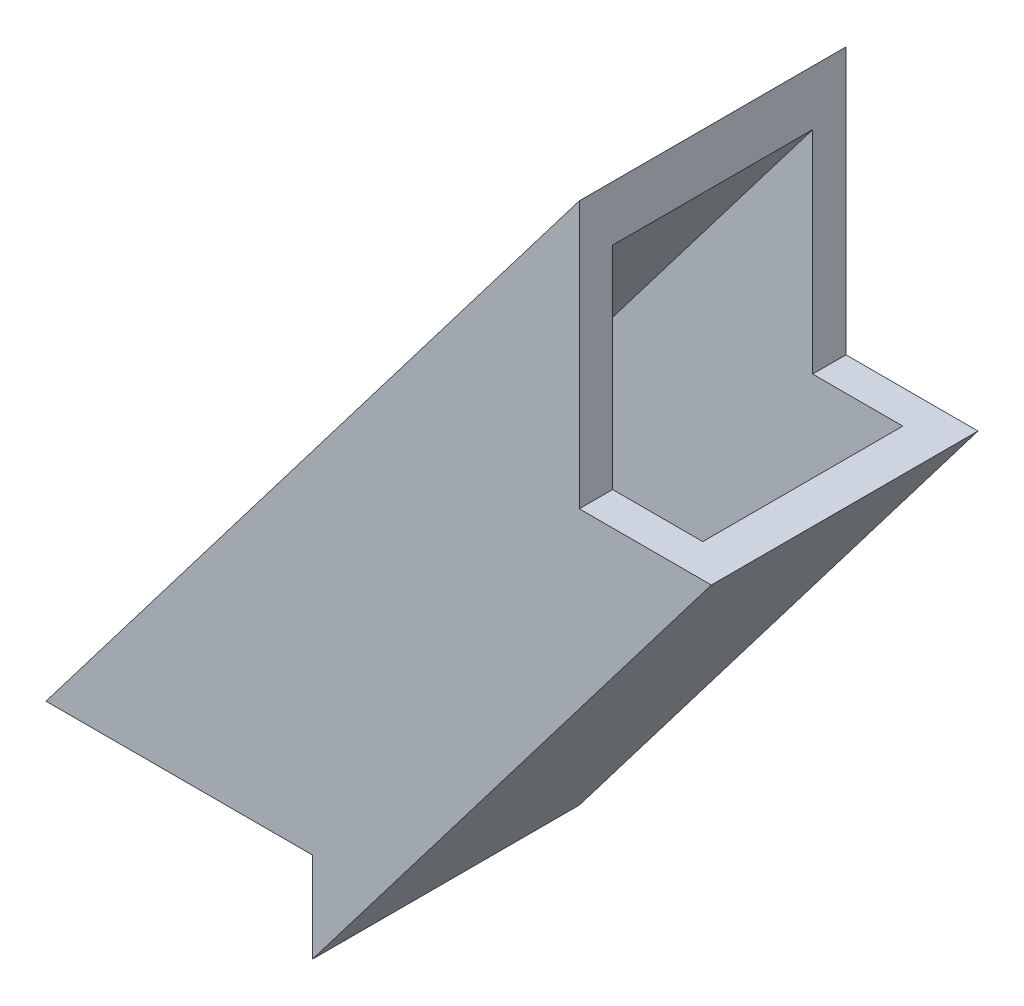
SolidWorks part; units mm, degrees
material "6061-T6 (SS)"
ref_plane "Front Plane" through (0, 0, 0) normal (0, 0, 1) x (1, 0, 0)
ref_plane "Top Plane" through (0, 0, 0) normal (0, 1, 0) x (1, 0, 0)
ref_plane "Right Plane" through (0, 0, 0) normal (1, 0, 0) x (0, 0, -1)
ref_plane "Plane1" through (115.3963, 151.4577, 0) normal (-0.606, -0.7954, 0) x (-0.7954, 0.606, 0)
sketch "Sketch1" plane through (115.3963, 151.4577, 0) normal (-0.606, -0.7954, 0) x (-0.7954, 0.606, 0)
  line L0 (15.3935, -101.6) -> (15.3935, -76.2) construction
  line L1 (-222.1481, -76.2) -> (-196.7481, -76.2)
  line L2 (-222.1481, -76.2) -> (-222.1481, -101.6)
  line L3 (-222.1481, -101.6) -> (-196.7481, -101.6)
  line L4 (-196.7481, -76.2) -> (-196.7481, -101.6)
  line L5 (-222.1481, -76.2) -> (-196.7481, -101.6) construction
  line L6 (-222.1481, -101.6) -> (-196.7481, -76.2) construction
  line L9 (-196.7481, 0) -> (-222.1481, 0) construction
  line L10 (-196.7481, -76.2) -> (-196.7481, 0) construction
  line L11 (-199.9231, -79.375) -> (-199.9231, -98.425)
  line L12 (-218.9731, -98.425) -> (-199.9231, -98.425)
  line L13 (-218.9731, -79.375) -> (-218.9731, -98.425)
  line L14 (-218.9731, -79.375) -> (-199.9231, -79.375)
  point P0 (-209.4481, -88.9)
  dimension "D1" = 3.175
extrude "Boss-Extrude1" add sketch "Sketch1" against normal up to vertex (75.2487 mm away) and the other way up to vertex (8.5737 mm away)
sketch "Sketch2" plane through (0, 0, 0) normal (0, 0, 1) x (1, 0, 0)
  line L0 (342.9, 92.075) -> (317.5, 92.075) construction
  line L1 (317.5, 92.075) -> (317.5, 66.675) construction
  line L2 (342.9, 66.675) -> (317.5, 66.675) construction
  line L3 (342.9, 92.075) -> (342.9, 66.675) construction
  line L4 (292.1, 25.4) -> (266.7, 25.4) construction
  line L5 (266.7, -25.4) -> (266.7, 25.4) construction
  line L6 (292.1, -25.4) -> (266.7, -25.4) construction
  line L7 (292.1, -25.4) -> (292.1, 25.4) construction
  line L8 (342.9, 92.075) -> (317.5, 92.075)
  line L9 (317.5, 92.075) -> (317.5, 66.675)
  line L10 (342.9, 66.675) -> (317.5, 66.675)
  line L11 (342.9, 92.075) -> (342.9, 66.675)
  line L12 (292.1, 25.4) -> (266.7, 25.4)
  line L13 (266.7, -25.4) -> (266.7, 25.4)
  line L14 (292.1, -25.4) -> (266.7, -25.4)
  line L15 (292.1, -25.4) -> (292.1, 25.4)
extrude "Cut-Extrude1" cut sketch "Sketch2" along normal through all
